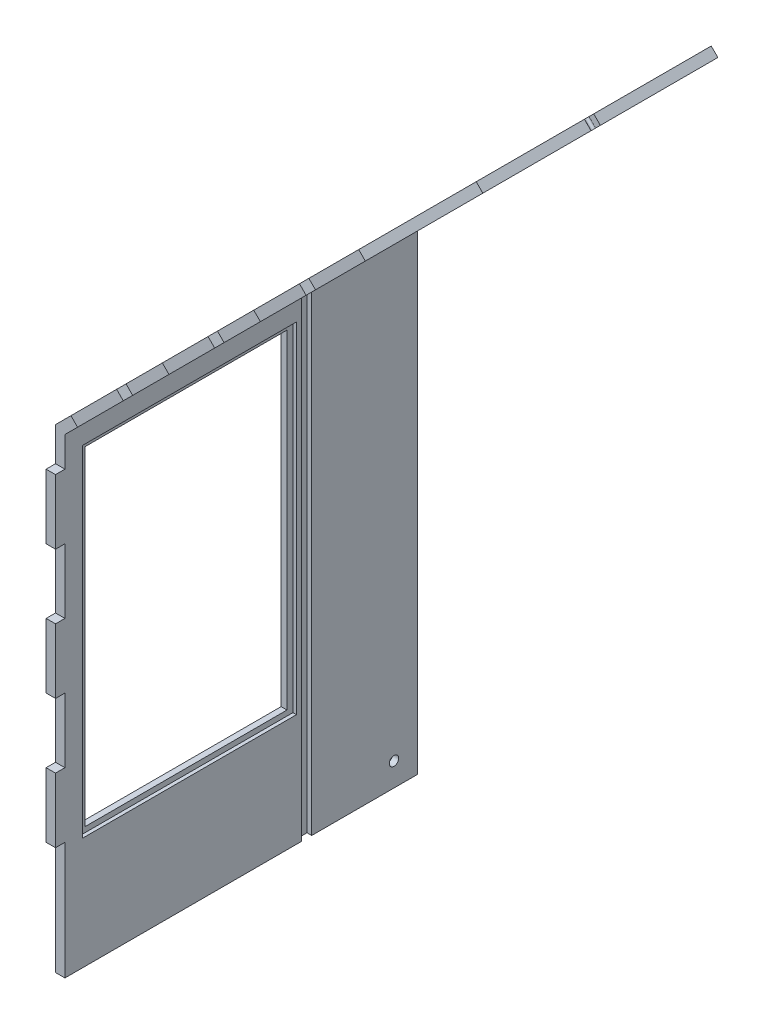
SolidWorks part; units mm, degrees
ref_plane "Plan de face" through (0, 0, 0) normal (0, 0, 1) x (1, 0, 0)
ref_plane "Plan de dessus" through (0, 0, 0) normal (0, 1, 0) x (1, 0, 0)
ref_plane "Plan de droite" through (0, 0, 0) normal (1, 0, 0) x (0, 0, -1)
sketch "Esquisse1" plane through (0, 0, 0) normal (0, 0, 1) x (1, 0, 0)
  line L0 (-21.9964, 361.3963) -> (82.3466, 361.3963) construction
  line L1 (-49.9708, -42.4537) -> (-57.9708, -42.4537)
  line L2 (200.0292, 619.3963) -> (205.686, 613.7395)
  line L3 (-35.3307, -42.4537) -> (82.3466, -42.4537) construction
  line L4 (-57.9708, -42.4537) -> (-57.9708, 361.3963)
  line L6 (-57.9708, 361.3963) -> (200.0292, 619.3963)
  line L11 (-49.9708, -42.4537) -> (-49.9708, 358.0826)
  line L13 (-49.9708, 358.0826) -> (205.686, 613.7395)
  dimension "D1" = 135
  dimension "D2" = 403.85
  dimension "D4" = 8
  dimension "D5" = 8
extrude "Boss.-Extru.1" add sketch "Esquisse1" along normal blind 308
sketch "Esquisse2" plane through (0, 0, 308) normal (0, 0, 1) x (1, 0, 0)
  line L0 (-57.9708, 361.3963) -> (-57.9708, -42.4537) construction
  line L1 (-57.9708, 57.5463) -> (-49.9708, 57.5463)
  line L2 (-57.9708, 57.5463) -> (-57.9708, -42.4537)
  line L3 (-57.9708, -42.4537) -> (-49.9708, -42.4537)
  line L4 (-49.9708, 57.5463) -> (-49.9708, -42.4537)
  line L5 (-57.9708, 222.5463) -> (-49.9708, 222.5463) construction
  line L6 (-49.9708, -42.4537) -> (-49.9708, 358.0826) construction
  line L7 (-57.9708, 167.5463) -> (-49.9708, 167.5463) construction
  line L8 (-57.9708, 277.5463) -> (-49.9708, 277.5463) construction
  line L9 (-57.9708, 332.5463) -> (-49.9708, 332.5463) construction
  line L10 (-57.9708, 112.5463) -> (-49.9708, 112.5463) construction
  line L11 (205.686, 613.7395) -> (163.2596, 571.3131)
  line L12 (-57.9708, 167.5463) -> (-49.9708, 167.5463)
  line L13 (-57.9708, 167.5463) -> (-57.9708, 112.5463)
  line L14 (-57.9708, 112.5463) -> (-49.9708, 112.5463)
  line L15 (-49.9708, 167.5463) -> (-49.9708, 112.5463)
  line L16 (-57.9708, 277.5463) -> (-49.9708, 277.5463)
  line L17 (-57.9708, 277.5463) -> (-57.9708, 222.5463)
  line L18 (-57.9708, 222.5463) -> (-49.9708, 222.5463)
  line L19 (-49.9708, 277.5463) -> (-49.9708, 222.5463)
  line L20 (-49.9708, 358.0826) -> (205.686, 613.7395) construction
  line L21 (163.2596, 571.3131) -> (157.6028, 576.9699)
  line L22 (200.0292, 619.3963) -> (-57.9708, 361.3963) construction
  line L23 (157.6028, 576.9699) -> (200.0292, 619.3963)
  line L24 (205.686, 613.7395) -> (200.0292, 619.3963)
  line L25 (118.7119, 538.079) -> (124.3688, 532.4222) construction
  line L26 (79.821, 499.1882) -> (85.4779, 493.5313) construction
  line L27 (40.9302, 460.2973) -> (46.587, 454.6404) construction
  line L28 (2.0393, 421.4064) -> (7.6961, 415.7496) construction
  line L29 (-36.8516, 382.5156) -> (-31.1947, 376.8587) construction
  line L30 (118.7119, 538.079) -> (124.3688, 532.4222)
  line L31 (124.3688, 532.4222) -> (85.4779, 493.5313)
  line L32 (85.4779, 493.5313) -> (79.821, 499.1882)
  line L33 (79.821, 499.1882) -> (118.7119, 538.079)
  line L34 (40.9302, 460.2973) -> (46.587, 454.6404)
  line L35 (46.587, 454.6404) -> (7.6961, 415.7496)
  line L36 (7.6961, 415.7496) -> (2.0393, 421.4064)
  line L37 (2.0393, 421.4064) -> (40.9302, 460.2973)
  line L38 (-36.8516, 382.5156) -> (-31.1947, 376.8587)
  line L39 (-31.1947, 376.8587) -> (-49.9708, 358.0826)
  line L40 (-49.9708, 358.0826) -> (-49.9708, 332.5463)
  line L41 (-49.9708, 332.5463) -> (-57.9708, 332.5463)
  line L42 (-57.9708, 332.5463) -> (-57.9708, 361.3963)
  line L43 (-57.9708, 361.3963) -> (-36.8516, 382.5156)
  dimension "D1" = 100
  dimension "D2" = 55
  dimension "D3" = 55
  dimension "D4" = 55
  dimension "D5" = 55
  dimension "D6" = 55
  dimension "D8" = 55
  dimension "D9" = 55
  dimension "D10" = 55
  dimension "D11" = 55
  dimension "D12" = 55
extrude "Enlèv. mat.-Extru.1" cut sketch "Esquisse2" against normal blind 8
sketch "Esquisse3" plane through (-57.9708, 0, 0) normal (-1, 0, 0) x (0, 0, 1)
  line L1 (308, 57.5463) -> (308, 112.5463) construction
  line L2 (280, 337.5463) -> (108, 337.5463)
  line L4 (280, 337.5463) -> (280, 57.5463)
  line L5 (280, 57.5463) -> (108, 57.5463)
  line L7 (108, 337.5463) -> (108, 57.5463)
  line L8 (300, -42.4537) -> (0, -42.4537) construction
  dimension "D1" = 28
  dimension "D2" = 100
  dimension "D3" = 172
  dimension "D4" = 280
extrude "Enlèv. mat.-Extru.2" cut sketch "Esquisse3" against normal blind 532
sketch "Esquisse4" plane through (-209.6836, 209.6836, 0) normal (-0.7071, 0.7071, 0) x (0, 0, 1)
  line L0 (308, 409.4213) -> (308, 354.4213) construction
  line L1 (81, 519.4213) -> (280, 519.4213)
  line L2 (81, 519.4213) -> (81, 244.4213)
  line L3 (81, 244.4213) -> (280, 244.4213)
  line L4 (280, 519.4213) -> (280, 244.4213)
  line L7 (308, 244.4213) -> (0, 244.4213) construction
  line L10 (0, 579.4213) -> (0, 214.5542) construction
  line L11 (300, 214.5542) -> (0, 214.5542) construction
  circle A0 centre (79.7175, 533.4213) radius 1
  circle A1 centre (274.9123, 533.4213) radius 1
  dimension "D1" = 28
  dimension "D2" = 199
extrude "Enlèv. mat.-Extru.3" cut sketch "Esquisse4" against normal blind 8
sketch "Esquisse5" plane through (-209.6836, 209.6836, 0) normal (-0.7071, 0.7071, 0) x (0, 0, 1)
  line L0 (150, 601.3113) -> (150, 527.8524) construction
  line L1 (200, 601.3113) -> (200, 567.2263) construction
  line L2 (100, 601.3113) -> (100, 564.5818) construction
  line L3 (93.5544, 571.4213) -> (206.5482, 571.4213) construction
  line L4 (300, 579.4213) -> (0, 579.4213) construction
  line L5 (250, 601.3113) -> (250, 567.2263) construction
  line L6 (100, 580.6695) -> (200, 580.6695)
  line L7 (100, 580.6695) -> (100, 573.6841)
  line L8 (102.2627, 571.4213) -> (197.7373, 571.4213)
  line L9 (200, 580.6695) -> (200, 573.6841)
  line L10 (268.0089, 575.4213) -> (244.0467, 575.4213) construction
  line L11 (100, 571.4213) -> (108.6541, 580.0754) construction
  circle A0 centre (250, 575.4213) radius 1.6
  circle A1 centre (50, 575.4213) radius 1.6
  arc A2 (100, 573.6841) -> (102.2627, 571.4213) centre (101.1314, 572.5527) ccw
  arc A3 (200, 573.6841) -> (197.7373, 571.4213) centre (198.8686, 572.5527) cw
  dimension "D6" = 45
  dimension "D1" = 50
  dimension "D2" = 50
  dimension "D3" = 8
  dimension "D4" = 4
  dimension "D5" = 50
extrude "Enlèv. mat.-Extru.4" cut sketch "Esquisse5" against normal blind 8
sketch "Esquisse6" plane through (-49.9708, 0, 0) normal (1, 0, 0) x (0, 0, -1)
  line L0 (-280, 57.5463) -> (-280, 337.5463) construction
  line L1 (-285, 342.5463) -> (-103, 342.5463)
  line L2 (-285, 342.5463) -> (-285, 53.0826)
  line L3 (-285, 53.0826) -> (-103, 53.0826)
  line L4 (-103, 342.5463) -> (-103, 53.0826)
  line L5 (-280, 337.5463) -> (-108, 337.5463) construction
  dimension "D1" = 5
  dimension "D2" = 5
extrude "Enlèv. mat.-Extru.5" cut sketch "Esquisse6" against normal blind 3
sketch "Esquisse7" plane through (-49.9708, 0, 0) normal (1, 0, 0) x (0, 0, -1)
  line L0 (-20, -50.9679) -> (-20, -18.7001) construction
  line L1 (16.5201, -22.4537) -> (-25.66, -22.4537) construction
  line L2 (-300, -42.4537) -> (0, -42.4537) construction
  line L3 (0, -42.4537) -> (0, 358.0826) construction
  circle A0 centre (-20, -22.4537) radius 4
  dimension "D1" = 20
  dimension "D2" = 20
extrude "Enlèv. mat.-Extru.6" cut sketch "Esquisse7" against normal blind 5.3
sketch "Esquisse8" plane through (-49.9708, 0, 0) normal (1, 0, 0) x (0, 0, -1)
  line L0 (-98.5, -65.768) -> (-98.5, 369.5018) construction
  line L1 (-90, -65.768) -> (-90, 369.5018) construction
  line L2 (0, -42.4537) -> (0, 358.0826) construction
  line L4 (-98.5, -48.7426) -> (-90, -48.7426)
  line L5 (-98.5, -48.7426) -> (-98.5, 359.0163)
  line L6 (-98.5, 359.0163) -> (-90, 359.0163)
  line L7 (-90, -48.7426) -> (-90, 359.0163)
  dimension "D1" = 8.5
  dimension "D2" = 90
extrude "Enlèv. mat.-Extru.7" cut sketch "Esquisse8" against normal blind 4
sketch "Esquisse9" plane through (-204.0267, 204.0267, 0) normal (0.7071, -0.7071, 0) x (0, 0, -1)
  line L0 (-98.5, 217.8679) -> (-98.5, 594.1023) construction
  line L1 (-90, 217.8679) -> (-90, 594.1023) construction
  line L2 (-100, 579.4213) -> (0, 579.4213) construction
  line L4 (-98.5, 215.6998) -> (-98.5, -68.1824) construction
  line L5 (-90, 571.4213) -> (-98.5, 571.4213)
  line L6 (-90, 571.4213) -> (-90, 215.7323)
  line L7 (-90, 215.7323) -> (-98.5, 215.7323)
  line L8 (-98.5, 571.4213) -> (-98.5, 215.7323)
  dimension "D1" = 8
extrude "Enlèv. mat.-Extru.8" cut sketch "Esquisse9" against normal blind 4
